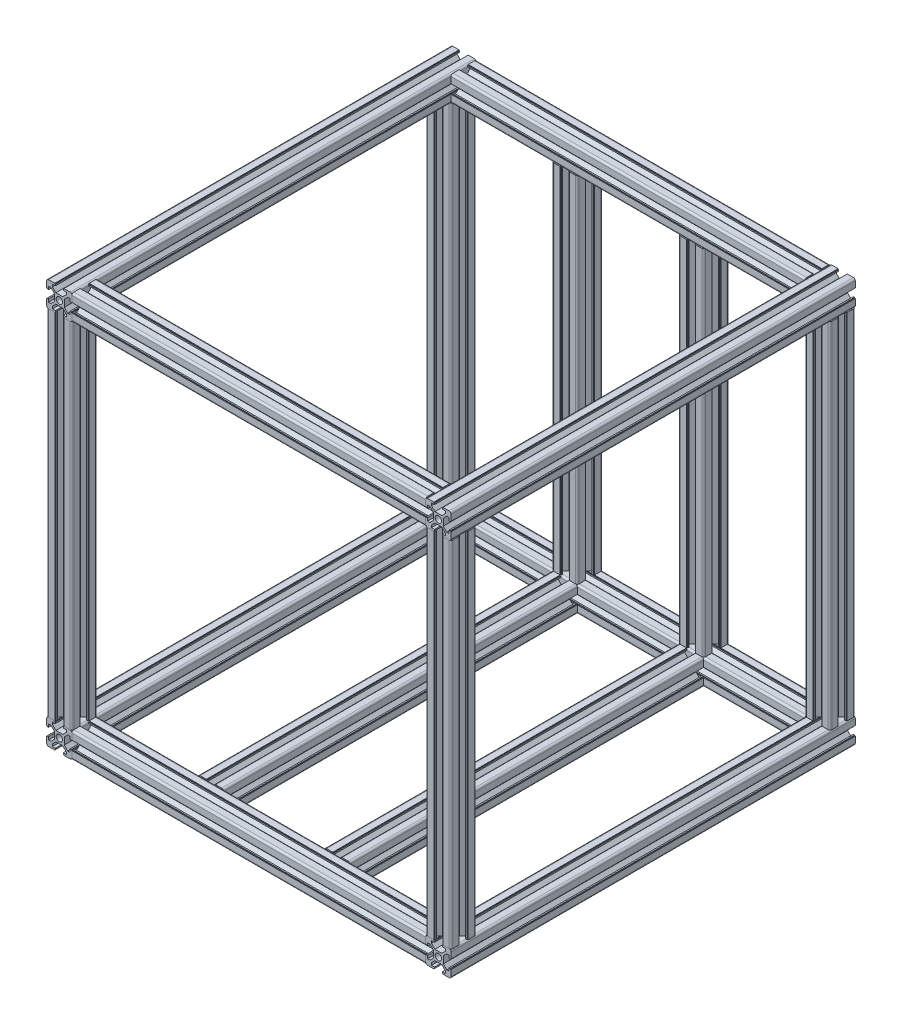
SolidWorks part; units mm, degrees
ref_plane "前视基准面" through (0, 0, 0) normal (0, 0, 1) x (1, 0, 0)
ref_plane "上视基准面" through (0, 0, 0) normal (0, 1, 0) x (1, 0, 0)
ref_plane "右视基准面" through (0, 0, 0) normal (1, 0, 0) x (0, 0, -1)
other "Configuration Table"
sketch3d "3D草图1"
  line L0 (0, 0, 0) -> (300, 0, 0)
  line L1 (300, 0, 0) -> (300, 300, 0)
  line L2 (300, 300, 0) -> (0, 300, 0)
  line L3 (0, 300, 0) -> (0, 0, 0)
  line L4 (0, 0, -300) -> (300, 0, -300)
  line L5 (300, 0, -300) -> (300, 300, -300)
  line L6 (300, 300, -300) -> (0, 300, -300)
  line L7 (0, 300, -300) -> (0, 0, -300)
  line L8 (0, 300, -300) -> (0, 300, 0)
  line L9 (300, 300, -300) -> (300, 300, 0)
  line L10 (300, 0, -300) -> (300, 0, 0)
  line L11 (0, 0, 0) -> (0, 0, -300)
  dimension "D1" = 300
  dimension "D2" = 300
  dimension "D3" = 300
other "铝型材 20 X 20 X R1.5(1)"
ref_plane "基准面2" through (0, 300, -300) normal (0, 0, 1) x (1, 0, 0)
sketch "Sketch11" plane through (0, 300, -300) normal (0, 0, 1) x (1, 0, 0)
  line L0 (-3.6, 10) -> (-3.6, 9.5)
  line L1 (-3.6, 9.5) -> (-3.1, 9.5)
  line L2 (-3.1, 9.5) -> (-3.1, 8.5)
  line L3 (-3.1, 8.5) -> (-5.5, 8.5)
  line L4 (-8.5, -10) -> (-3.6, -10)
  line L5 (-10, -8.5) -> (-10, -3.6)
  line L6 (8.5, 10) -> (3.6, 10)
  line L7 (10, 8.5) -> (10, 3.6)
  line L8 (0, 14.8756) -> (0, 0) construction
  line L9 (0, 0) -> (14.1675, 0) construction
  line L10 (-5.5, 8.5) -> (-5.5, 6.65)
  line L11 (-5.5, 6.65) -> (-2.75, 3.9)
  line L12 (-2.75, 3.9) -> (2.75, 3.9)
  line L13 (5.5, 6.65) -> (2.75, 3.9)
  line L14 (5.5, 8.5) -> (5.5, 6.65)
  line L15 (3.1, 8.5) -> (5.5, 8.5)
  line L16 (3.1, 9.5) -> (3.1, 8.5)
  line L17 (3.6, 9.5) -> (3.1, 9.5)
  line L18 (3.6, 10) -> (3.6, 9.5)
  line L19 (-3.6, 10) -> (-8.5, 10)
  line L20 (10, 3.6) -> (9.5, 3.6)
  line L21 (9.5, 3.6) -> (9.5, 3.1)
  line L22 (9.5, 3.1) -> (8.5, 3.1)
  line L23 (8.5, 3.1) -> (8.5, 5.5)
  line L24 (8.5, 5.5) -> (6.65, 5.5)
  line L25 (6.65, 5.5) -> (3.9, 2.75)
  line L26 (3.9, 2.75) -> (3.9, -2.75)
  line L27 (6.65, -5.5) -> (3.9, -2.75)
  line L28 (8.5, -5.5) -> (6.65, -5.5)
  line L29 (8.5, -3.1) -> (8.5, -5.5)
  line L30 (9.5, -3.1) -> (8.5, -3.1)
  line L31 (9.5, -3.6) -> (9.5, -3.1)
  line L32 (10, -3.6) -> (9.5, -3.6)
  line L33 (3.6, -10) -> (3.6, -9.5)
  line L34 (3.6, -9.5) -> (3.1, -9.5)
  line L35 (3.1, -9.5) -> (3.1, -8.5)
  line L36 (3.1, -8.5) -> (5.5, -8.5)
  line L37 (5.5, -8.5) -> (5.5, -6.65)
  line L38 (5.5, -6.65) -> (2.75, -3.9)
  line L39 (2.75, -3.9) -> (-2.75, -3.9)
  line L40 (-5.5, -6.65) -> (-2.75, -3.9)
  line L41 (-5.5, -8.5) -> (-5.5, -6.65)
  line L42 (-3.1, -8.5) -> (-5.5, -8.5)
  line L43 (-3.1, -9.5) -> (-3.1, -8.5)
  line L44 (-3.6, -9.5) -> (-3.1, -9.5)
  line L45 (-3.6, -10) -> (-3.6, -9.5)
  line L46 (-10, -3.6) -> (-9.5, -3.6)
  line L47 (-9.5, -3.6) -> (-9.5, -3.1)
  line L48 (-9.5, -3.1) -> (-8.5, -3.1)
  line L49 (-8.5, -3.1) -> (-8.5, -5.5)
  line L50 (-8.5, -5.5) -> (-6.65, -5.5)
  line L51 (-6.65, -5.5) -> (-3.9, -2.75)
  line L52 (-3.9, -2.75) -> (-3.9, 2.75)
  line L53 (-6.65, 5.5) -> (-3.9, 2.75)
  line L54 (-8.5, 5.5) -> (-6.65, 5.5)
  line L55 (-8.5, 3.1) -> (-8.5, 5.5)
  line L56 (-9.5, 3.1) -> (-8.5, 3.1)
  line L57 (-9.5, 3.6) -> (-9.5, 3.1)
  line L58 (-10, 3.6) -> (-9.5, 3.6)
  line L59 (3.6, -10) -> (8.5, -10)
  line L60 (-10, 3.6) -> (-10, 8.5)
  line L61 (10, -3.6) -> (10, -8.5)
  circle A0 centre (0, 0) radius 2.5
  arc A1 (-10, 8.5) -> (-8.5, 10) centre (-8.5, 8.5) cw
  arc A2 (10, 8.5) -> (8.5, 10) centre (8.5, 8.5) ccw
  arc A3 (-8.5, -10) -> (-10, -8.5) centre (-8.5, -8.5) cw
  arc A4 (8.5, -10) -> (10, -8.5) centre (8.5, -8.5) ccw
  point P0 (-10, 0)
  point P1 (10, 0)
  point P2 (0, 10)
  point P3 (0, -10)
  point P4 (0, 0)
  point P5 (-10, -10)
  point P6 (10, -10)
  point P7 (10, 10)
  point P8 (-10, 10)
  point P13 (0, 0)
  point P36 (-10, 10)
  point P39 (10, 10)
  dimension "D1" = 11
  dimension "D2" = 20
  dimension "D3" = 6.2
  dimension "D4" = 7.2
  dimension "D5" = 6.1
  dimension "D6" = 5
  dimension "D7" = 1.5
  dimension "D8" = 45
  dimension "D9" = 0.5
  dimension "D10" = 1
  dimension "D11" = 5.5
other "剪裁/延伸1"
sketch3d "3D草图2"
  line L0 (0, 0, -300) -> (300, 0, -300) construction
  line L1 (150, 0, -300) -> (150, 300, -300) construction
  line L2 (300, 300, -300) -> (0, 300, -300) construction
  line L3 (200, 0, -300) -> (200, 300, -300)
  line L4 (100, 300, -300) -> (100, 0, -300)
  dimension "D1" = 50
  dimension "D2" = 50
  dimension "D3" = 150
other "铝型材 20 X 20 X R1.5(3)"
ref_plane "基准面3" through (100, 300, -300) normal (0, -1, 0) x (1, 0, 0)
sketch "Sketch1" plane through (100, 300, -300) normal (0, -1, 0) x (1, 0, 0)
  line L0 (-3.6, 10) -> (-3.6, 9.5)
  line L1 (-3.6, 9.5) -> (-3.1, 9.5)
  line L2 (-3.1, 9.5) -> (-3.1, 8.5)
  line L3 (-3.1, 8.5) -> (-5.5, 8.5)
  line L4 (-8.5, -10) -> (-3.6, -10)
  line L5 (-10, -8.5) -> (-10, -3.6)
  line L6 (8.5, 10) -> (3.6, 10)
  line L7 (10, 8.5) -> (10, 3.6)
  line L8 (0, 14.8756) -> (0, 0) construction
  line L9 (0, 0) -> (14.1675, 0) construction
  line L10 (-5.5, 8.5) -> (-5.5, 6.65)
  line L11 (-5.5, 6.65) -> (-2.75, 3.9)
  line L12 (-2.75, 3.9) -> (2.75, 3.9)
  line L13 (5.5, 6.65) -> (2.75, 3.9)
  line L14 (5.5, 8.5) -> (5.5, 6.65)
  line L15 (3.1, 8.5) -> (5.5, 8.5)
  line L16 (3.1, 9.5) -> (3.1, 8.5)
  line L17 (3.6, 9.5) -> (3.1, 9.5)
  line L18 (3.6, 10) -> (3.6, 9.5)
  line L19 (-3.6, 10) -> (-8.5, 10)
  line L20 (10, 3.6) -> (9.5, 3.6)
  line L21 (9.5, 3.6) -> (9.5, 3.1)
  line L22 (9.5, 3.1) -> (8.5, 3.1)
  line L23 (8.5, 3.1) -> (8.5, 5.5)
  line L24 (8.5, 5.5) -> (6.65, 5.5)
  line L25 (6.65, 5.5) -> (3.9, 2.75)
  line L26 (3.9, 2.75) -> (3.9, -2.75)
  line L27 (6.65, -5.5) -> (3.9, -2.75)
  line L28 (8.5, -5.5) -> (6.65, -5.5)
  line L29 (8.5, -3.1) -> (8.5, -5.5)
  line L30 (9.5, -3.1) -> (8.5, -3.1)
  line L31 (9.5, -3.6) -> (9.5, -3.1)
  line L32 (10, -3.6) -> (9.5, -3.6)
  line L33 (3.6, -10) -> (3.6, -9.5)
  line L34 (3.6, -9.5) -> (3.1, -9.5)
  line L35 (3.1, -9.5) -> (3.1, -8.5)
  line L36 (3.1, -8.5) -> (5.5, -8.5)
  line L37 (5.5, -8.5) -> (5.5, -6.65)
  line L38 (5.5, -6.65) -> (2.75, -3.9)
  line L39 (2.75, -3.9) -> (-2.75, -3.9)
  line L40 (-5.5, -6.65) -> (-2.75, -3.9)
  line L41 (-5.5, -8.5) -> (-5.5, -6.65)
  line L42 (-3.1, -8.5) -> (-5.5, -8.5)
  line L43 (-3.1, -9.5) -> (-3.1, -8.5)
  line L44 (-3.6, -9.5) -> (-3.1, -9.5)
  line L45 (-3.6, -10) -> (-3.6, -9.5)
  line L46 (-10, -3.6) -> (-9.5, -3.6)
  line L47 (-9.5, -3.6) -> (-9.5, -3.1)
  line L48 (-9.5, -3.1) -> (-8.5, -3.1)
  line L49 (-8.5, -3.1) -> (-8.5, -5.5)
  line L50 (-8.5, -5.5) -> (-6.65, -5.5)
  line L51 (-6.65, -5.5) -> (-3.9, -2.75)
  line L52 (-3.9, -2.75) -> (-3.9, 2.75)
  line L53 (-6.65, 5.5) -> (-3.9, 2.75)
  line L54 (-8.5, 5.5) -> (-6.65, 5.5)
  line L55 (-8.5, 3.1) -> (-8.5, 5.5)
  line L56 (-9.5, 3.1) -> (-8.5, 3.1)
  line L57 (-9.5, 3.6) -> (-9.5, 3.1)
  line L58 (-10, 3.6) -> (-9.5, 3.6)
  line L59 (3.6, -10) -> (8.5, -10)
  line L60 (-10, 3.6) -> (-10, 8.5)
  line L61 (10, -3.6) -> (10, -8.5)
  circle A0 centre (0, 0) radius 2.5
  arc A1 (-10, 8.5) -> (-8.5, 10) centre (-8.5, 8.5) cw
  arc A2 (10, 8.5) -> (8.5, 10) centre (8.5, 8.5) ccw
  arc A3 (-8.5, -10) -> (-10, -8.5) centre (-8.5, -8.5) cw
  arc A4 (8.5, -10) -> (10, -8.5) centre (8.5, -8.5) ccw
  point P0 (-10, 0)
  point P1 (10, 0)
  point P2 (0, 10)
  point P3 (0, -10)
  point P4 (0, 0)
  point P5 (-10, -10)
  point P6 (10, -10)
  point P7 (10, 10)
  point P8 (-10, 10)
  point P13 (0, 0)
  point P36 (-10, 10)
  point P39 (10, 10)
  dimension "D1" = 11
  dimension "D2" = 20
  dimension "D3" = 6.2
  dimension "D4" = 7.2
  dimension "D5" = 6.1
  dimension "D6" = 5
  dimension "D7" = 1.5
  dimension "D8" = 45
  dimension "D9" = 0.5
  dimension "D10" = 1
  dimension "D11" = 5.5
other "剪裁/延伸2"
sketch3d "3D草图4"
  line L0 (100, 0, -300) -> (100, 0, 0)
  line L1 (0, 0, 0) -> (300, 0, 0) construction
  line L2 (200, 0, -300) -> (200, 0, 0)
  line L3 (0, 0, -300) -> (300, 0, -300) construction
other "铝型材 20 X 20 X R1.5(7)"
ref_plane "基准面5" through (100, 0, -300) normal (0, 0, 1) x (1, 0, 0)
sketch "Sketch13" plane through (100, 0, -300) normal (0, 0, 1) x (1, 0, 0)
  line L0 (-3.6, 10) -> (-3.6, 9.5)
  line L1 (-3.6, 9.5) -> (-3.1, 9.5)
  line L2 (-3.1, 9.5) -> (-3.1, 8.5)
  line L3 (-3.1, 8.5) -> (-5.5, 8.5)
  line L4 (-8.5, -10) -> (-3.6, -10)
  line L5 (-10, -8.5) -> (-10, -3.6)
  line L6 (8.5, 10) -> (3.6, 10)
  line L7 (10, 8.5) -> (10, 3.6)
  line L8 (0, 14.8756) -> (0, 0) construction
  line L9 (0, 0) -> (14.1675, 0) construction
  line L10 (-5.5, 8.5) -> (-5.5, 6.65)
  line L11 (-5.5, 6.65) -> (-2.75, 3.9)
  line L12 (-2.75, 3.9) -> (2.75, 3.9)
  line L13 (5.5, 6.65) -> (2.75, 3.9)
  line L14 (5.5, 8.5) -> (5.5, 6.65)
  line L15 (3.1, 8.5) -> (5.5, 8.5)
  line L16 (3.1, 9.5) -> (3.1, 8.5)
  line L17 (3.6, 9.5) -> (3.1, 9.5)
  line L18 (3.6, 10) -> (3.6, 9.5)
  line L19 (-3.6, 10) -> (-8.5, 10)
  line L20 (10, 3.6) -> (9.5, 3.6)
  line L21 (9.5, 3.6) -> (9.5, 3.1)
  line L22 (9.5, 3.1) -> (8.5, 3.1)
  line L23 (8.5, 3.1) -> (8.5, 5.5)
  line L24 (8.5, 5.5) -> (6.65, 5.5)
  line L25 (6.65, 5.5) -> (3.9, 2.75)
  line L26 (3.9, 2.75) -> (3.9, -2.75)
  line L27 (6.65, -5.5) -> (3.9, -2.75)
  line L28 (8.5, -5.5) -> (6.65, -5.5)
  line L29 (8.5, -3.1) -> (8.5, -5.5)
  line L30 (9.5, -3.1) -> (8.5, -3.1)
  line L31 (9.5, -3.6) -> (9.5, -3.1)
  line L32 (10, -3.6) -> (9.5, -3.6)
  line L33 (3.6, -10) -> (3.6, -9.5)
  line L34 (3.6, -9.5) -> (3.1, -9.5)
  line L35 (3.1, -9.5) -> (3.1, -8.5)
  line L36 (3.1, -8.5) -> (5.5, -8.5)
  line L37 (5.5, -8.5) -> (5.5, -6.65)
  line L38 (5.5, -6.65) -> (2.75, -3.9)
  line L39 (2.75, -3.9) -> (-2.75, -3.9)
  line L40 (-5.5, -6.65) -> (-2.75, -3.9)
  line L41 (-5.5, -8.5) -> (-5.5, -6.65)
  line L42 (-3.1, -8.5) -> (-5.5, -8.5)
  line L43 (-3.1, -9.5) -> (-3.1, -8.5)
  line L44 (-3.6, -9.5) -> (-3.1, -9.5)
  line L45 (-3.6, -10) -> (-3.6, -9.5)
  line L46 (-10, -3.6) -> (-9.5, -3.6)
  line L47 (-9.5, -3.6) -> (-9.5, -3.1)
  line L48 (-9.5, -3.1) -> (-8.5, -3.1)
  line L49 (-8.5, -3.1) -> (-8.5, -5.5)
  line L50 (-8.5, -5.5) -> (-6.65, -5.5)
  line L51 (-6.65, -5.5) -> (-3.9, -2.75)
  line L52 (-3.9, -2.75) -> (-3.9, 2.75)
  line L53 (-6.65, 5.5) -> (-3.9, 2.75)
  line L54 (-8.5, 5.5) -> (-6.65, 5.5)
  line L55 (-8.5, 3.1) -> (-8.5, 5.5)
  line L56 (-9.5, 3.1) -> (-8.5, 3.1)
  line L57 (-9.5, 3.6) -> (-9.5, 3.1)
  line L58 (-10, 3.6) -> (-9.5, 3.6)
  line L59 (3.6, -10) -> (8.5, -10)
  line L60 (-10, 3.6) -> (-10, 8.5)
  line L61 (10, -3.6) -> (10, -8.5)
  circle A0 centre (0, 0) radius 2.5
  arc A1 (-10, 8.5) -> (-8.5, 10) centre (-8.5, 8.5) cw
  arc A2 (10, 8.5) -> (8.5, 10) centre (8.5, 8.5) ccw
  arc A3 (-8.5, -10) -> (-10, -8.5) centre (-8.5, -8.5) cw
  arc A4 (8.5, -10) -> (10, -8.5) centre (8.5, -8.5) ccw
  point P0 (-10, 0)
  point P1 (10, 0)
  point P2 (0, 10)
  point P3 (0, -10)
  point P4 (0, 0)
  point P5 (-10, -10)
  point P6 (10, -10)
  point P7 (10, 10)
  point P8 (-10, 10)
  point P13 (0, 0)
  point P36 (-10, 10)
  point P39 (10, 10)
  dimension "D1" = 11
  dimension "D2" = 20
  dimension "D3" = 6.2
  dimension "D4" = 7.2
  dimension "D5" = 6.1
  dimension "D6" = 5
  dimension "D7" = 1.5
  dimension "D8" = 45
  dimension "D9" = 0.5
  dimension "D10" = 1
  dimension "D11" = 5.5
other "剪裁/延伸7"
other "剪裁/延伸8"
sketch "草图1" plane through (0, 0, 10) normal (0, 0, 1) x (1, 0, 0)
  circle A0 centre (150, 150) radius 84.8171 construction
